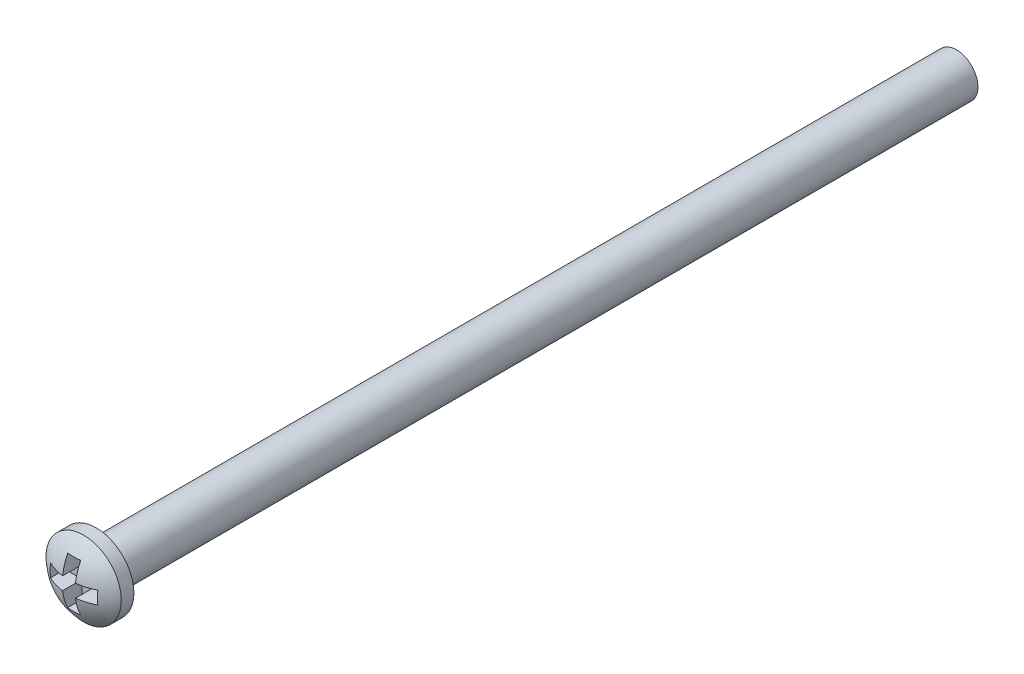
SolidWorks part; units mm, degrees
ref_plane "前视基准面" through (0, 0, 0) normal (0, 0, 1) x (1, 0, 0)
ref_plane "上视基准面" through (0, 0, 0) normal (0, 1, 0) x (1, 0, 0)
ref_plane "右视基准面" through (0, 0, 0) normal (1, 0, 0) x (0, 0, -1)
other "Configuration Table"
sketch "草图1" plane through (0, 0, 0) normal (0, 0, 1) x (1, 0, 0)
  circle A0 centre (0, 0) radius 1
extrude "标准杆径_头下长度" add sketch "草图1" against normal blind 40
sketch "草图2" plane through (0, 0, 0) normal (0, 0, 1) x (1, 0, 0)
  circle A0 centre (0, 0) radius 1.9
sketch "草图4" plane through (0, 0, 0) normal (0, 1, 0) x (1, 0, 0)
  line L0 (0, 0) -> (2.25, 0)
  line L1 (2.25, 0) -> (2.25, -0.1843)
  line L2 (0, -1.2) -> (0, 0)
  line L3 (0, 2) -> (0, -3.2) construction
  arc A0 (2.25, -0.1843) -> (0, -1.2) centre (0, 1.8) cw
sketch "草图5" plane through (0, 0, 0) normal (0, 0, 1) x (1, 0, 0)
  line L0 (-0.3, -1.1) -> (0.3, -1.1)
  line L1 (0.3, -1.1) -> (0.3, -0.3)
  line L2 (0.3, -0.3) -> (1.1, -0.3)
  line L3 (1.1, -0.3) -> (1.1, 0.3)
  line L4 (1.1, 0.3) -> (0.3, 0.3)
  line L5 (0.3, 0.3) -> (0.3, 1.1)
  line L6 (0.3, 1.1) -> (-0.3, 1.1)
  line L7 (-0.3, 1.1) -> (-0.3, 0.3)
  line L8 (-0.3, 0.3) -> (-1.1, 0.3)
  line L9 (-1.1, 0.3) -> (-1.1, -0.3)
  line L10 (-1.1, -0.3) -> (-0.3, -0.3)
  line L11 (-0.3, -0.3) -> (-0.3, -1.1)
sketch "草图6" plane through (0, 0, 0) normal (0, 1, 0) x (1, 0, 0)
  line L0 (0, 0) -> (1.75, 0)
  line L1 (1.75, 0) -> (1.75, -0.5854)
  line L2 (0, -1.3) -> (0, 0)
  line L3 (0, 2) -> (0, -3.3) construction
  arc A0 (1.75, -0.5854) -> (0, -1.3) centre (0, 1.2) cw
revolve "已确认_十字槽盘头" add sketch "草图6" angle 360 about L3
sketch "草图7" plane through (0, 0, 0) normal (0, 0, 1) x (1, 0, 0)
  line L0 (-0.3, -1.1) -> (0.3, -1.1)
  line L1 (0.3, -1.1) -> (0.3, -0.3)
  line L2 (0.3, -0.3) -> (1.1, -0.3)
  line L3 (1.1, -0.3) -> (1.1, 0.3)
  line L4 (1.1, 0.3) -> (0.3, 0.3)
  line L5 (0.3, 0.3) -> (0.3, 1.1)
  line L6 (0.3, 1.1) -> (-0.3, 1.1)
  line L7 (-0.3, 1.1) -> (-0.3, 0.3)
  line L8 (-0.3, 0.3) -> (-1.1, 0.3)
  line L9 (-1.1, 0.3) -> (-1.1, -0.3)
  line L10 (-1.1, -0.3) -> (-0.3, -0.3)
  line L11 (-0.3, -0.3) -> (-0.3, -1.1)
extrude "十字槽_PH1_简化" cut sketch "草图7" against normal blind 0.96 from offset 1.31
